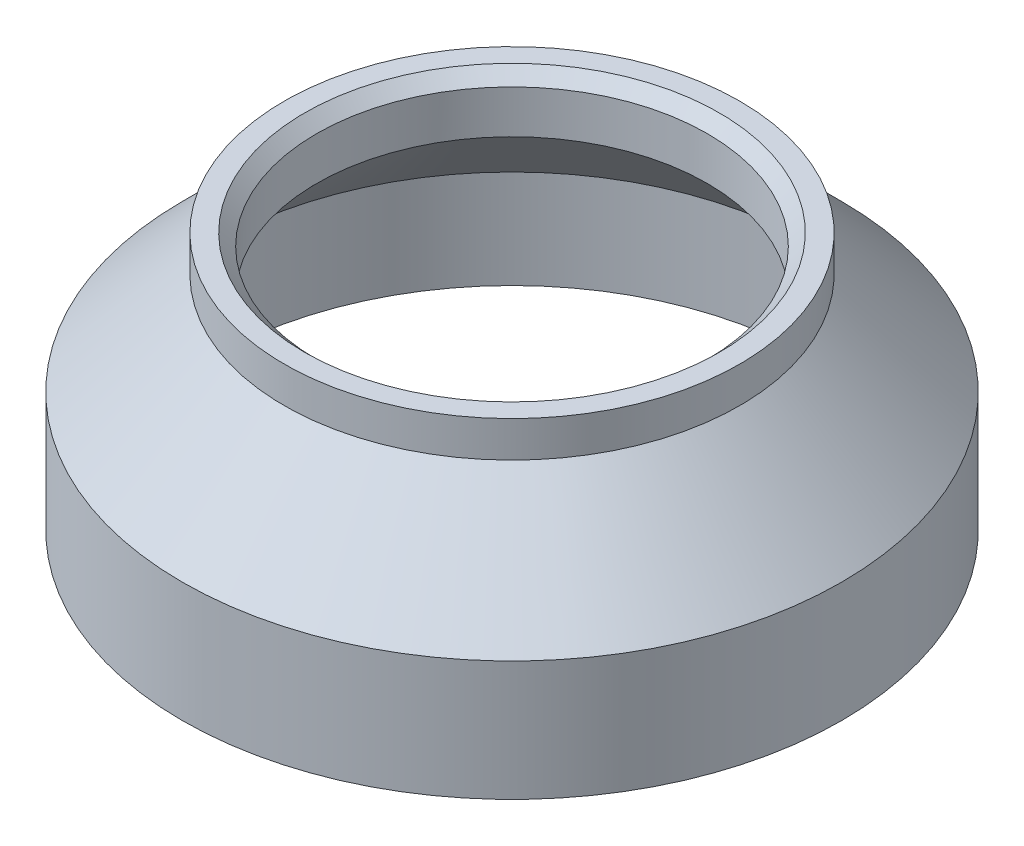
SolidWorks part; units mm, degrees
material "AISI 304"
ref_plane "Front Plane" through (0, 0, 0) normal (0, 0, 1) x (1, 0, 0)
ref_plane "Top Plane" through (0, 0, 0) normal (0, 1, 0) x (1, 0, 0)
ref_plane "Right Plane" through (0, 0, 0) normal (1, 0, 0) x (0, 0, -1)
sketch "Sketch2" plane through (0, 0, 0) normal (0, 0, 1) x (1, 0, 0)
  line L0 (34.925, 0) -> (34.925, 9.525)
  line L1 (34.925, 9.525) -> (24.13, 20.32)
  line L2 (34.925, -3.175) -> (31.75, -3.175)
  line L3 (34.925, 0) -> (34.925, -3.175)
  line L4 (31.75, -3.175) -> (31.75, 0)
  line L5 (0, 0) -> (0, 50000) construction
  line L6 (0, 0) -> (-50000, 0) construction
  line L7 (20.701, 18.288) -> (20.701, 24.13)
  line L8 (20.701, 24.13) -> (24.13, 24.13)
  line L9 (24.13, 24.13) -> (24.13, 20.32)
  line L10 (20.701, 18.288) -> (31.75, 7.239)
  line L12 (31.75, 0) -> (31.75, 7.239)
  dimension "D1" = 3.175
  dimension "D2" = 31.75
  dimension "D3" = 135
  dimension "D4" = 20.701
  dimension "D5" = 3.81
  dimension "D6" = 3.175
  dimension "D7" = 5.842
  dimension "D8" = 20.32
  dimension "D10" = 3.429
revolve "Revolve1" add sketch "Sketch2" angle 360 about L5
chamfer "Chamfer1" distance 1.27 angle 45 1 edges at (0, 24.13, -20.701)
